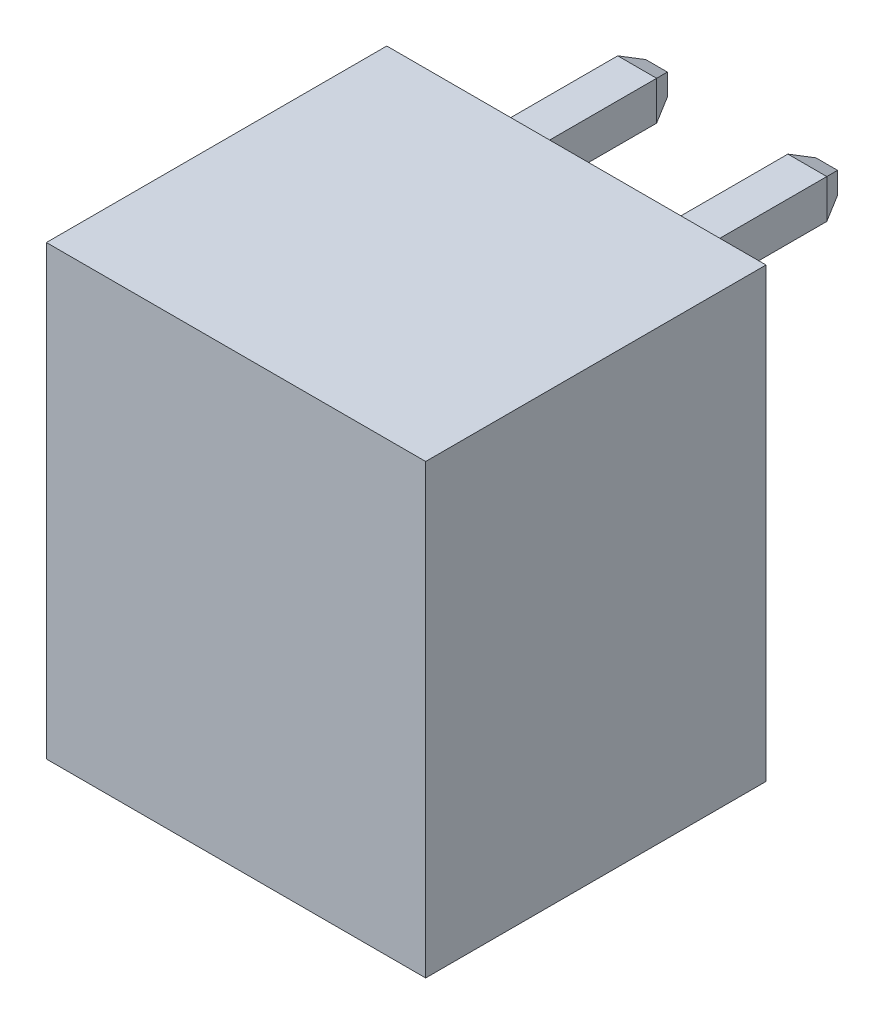
SolidWorks part; units mm, degrees
ref_plane "Спереди" through (0, 0, 0) normal (0, 0, 1) x (1, 0, 0)
ref_plane "Сверху" through (0, 0, 0) normal (0, 1, 0) x (1, 0, 0)
ref_plane "Справа" through (0, 0, 0) normal (1, 0, 0) x (0, 0, -1)
sketch "Эскиз1" plane through (0, 0, 0) normal (0, 0, 1) x (1, 0, 0)
  line L1 (3.9, 9.2) -> (-3.9, 9.2)
  line L2 (3.9, 9.2) -> (3.9, 0)
  line L3 (3.9, 0) -> (-3.9, 0)
  line L4 (-3.9, 9.2) -> (-3.9, 0)
  line L5 (3.9, 9.2) -> (-3.9, 0) construction
  line L6 (3.9, 0) -> (-3.9, 9.2) construction
  point P0 (0, 4.6)
  point P5 (0, 0)
  dimension "D1" = 9.2
  dimension "D2" = 7.8
extrude "Бобышка-Вытянуть1" add sketch "Эскиз1" along normal blind 7
sketch "Эскиз2" plane through (0, 0, 0) normal (0, 0, -1) x (-1, 0, 0)
  line L0 (3.9, 0) -> (-3.9, 0) construction
  line L1 (-2.15, 7.6) -> (-1.35, 7.6)
  line L2 (-2.15, 7.6) -> (-2.15, 8.4)
  line L3 (-2.15, 8.4) -> (-1.35, 8.4)
  line L4 (-1.35, 7.6) -> (-1.35, 8.4)
  line L5 (-2.15, 7.6) -> (-1.35, 8.4) construction
  line L6 (-2.15, 8.4) -> (-1.35, 7.6) construction
  line L7 (-3.9, 0) -> (-3.9, 9.2) construction
  point P0 (-1.75, 8)
  dimension "D1" = 8
  dimension "D2" = 0.8
  dimension "D3" = 2.15
extrude "Бобышка-Вытянуть2" add sketch "Эскиз2" along normal blind 3.4
chamfer "Фаска1" distance 0.4 angle 24 4 edges at (1.75, 8.4, -3.4) (1.35, 8, -3.4) (1.75, 7.6, -3.4) (2.15, 8, -3.4)
sketch "Эскиз3" plane through (0, 0, 0) normal (0, -1, 0) x (1, 0, 0)
  line L1 (0.15, 0.8) -> (3.25, 0.8)
  line L2 (0.15, 0.8) -> (0.15, 5)
  line L4 (3.25, 0.8) -> (3.25, 5)
  line L5 (0.15, 0.8) -> (3.25, 5) construction
  line L6 (0.15, 5) -> (3.25, 0.8) construction
  line L7 (-3.9, 0) -> (3.9, 0) construction
  line L9 (3.9, 7) -> (3.9, 0) construction
  line L10 (-3.9, 7) -> (3.9, 7) construction
  line L11 (0.15, 6.5) -> (3.25, 6.5)
  line L12 (0.15, 5) -> (1.15, 5)
  line L13 (1.15, 5) -> (0.15, 6.5)
  line L14 (3.25, 5) -> (2.25, 5)
  line L15 (2.25, 5) -> (3.25, 6.5)
  point P0 (1.7, 2.9)
  point P5 (1.7, 6.5)
  dimension "D1" = 2.2
  dimension "D2" = 0.8
  dimension "D3" = 2
  dimension "D4" = 3.1
  dimension "D5" = 0.5
  dimension "D6" = 1
extrude "Вырез-Вытянуть1" cut sketch "Эскиз3" against normal blind 7
pattern_linear "Линейный массив1" count 3 spacing 3.5 along (-1, 0, 0) of "Бобышка-Вытянуть2", "Фаска1"
pattern_linear "Линейный массив2" count 2 spacing 3.5 along (-1, 0, 0) of "Вырез-Вытянуть1"
sketch "Эскиз4" plane through (0, 7, 0) normal (0, -1, 0) x (1, 0, 0)
  line L0 (2.15, -3) -> (2.15, 0) construction
  line L1 (1.35, 3.4) -> (2.15, 3.4)
  line L2 (1.35, 3.4) -> (1.35, 2.6)
  line L3 (1.35, 2.6) -> (2.15, 2.6)
  line L4 (2.15, 3.4) -> (2.15, 2.6)
  line L5 (1.35, 3.4) -> (2.15, 2.6) construction
  line L6 (1.35, 2.6) -> (2.15, 3.4) construction
  line L7 (1.35, -3) -> (1.35, 0) construction
  line L8 (-3.9, 0) -> (3.9, 0) construction
  point P0 (1.75, 3)
  point P5 (0, 0)
  dimension "D1" = 3
extrude "Бобышка-Вытянуть3" add sketch "Эскиз4" along normal blind 6
chamfer "Фаска2" distance 0.4 angle 24 4 edges at (2.15, 1, 3) (1.75, 1, 3.4) (1.35, 1, 3) (1.75, 1, 2.6)
pattern_linear "Линейный массив3" count 2 spacing 3.5 along (-1, 0, 0) of "Фаска2", "Бобышка-Вытянуть3"
equation "\"n\"= 2"
equation "\"width\" = 3.5 * ( \"n\" - 1 ) + 4.3"
equation "\"D2@Эскиз1\" = 3.5 * ( \"n\" - 1 ) + 4.3"
